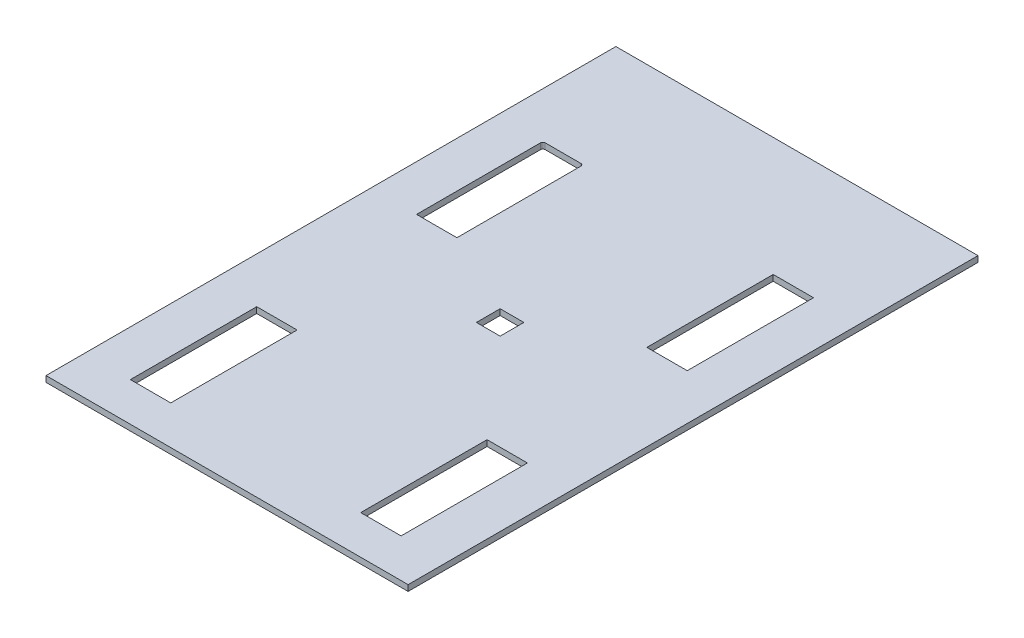
SolidWorks part; units mm, degrees
ref_plane "Front Plane" through (0, 0, 0) normal (0, 0, 1) x (1, 0, 0)
ref_plane "Top Plane" through (0, 0, 0) normal (0, 1, 0) x (1, 0, 0)
ref_plane "Right Plane" through (0, 0, 0) normal (1, 0, 0) x (0, 0, -1)
sketch "Sketch1" plane through (0, 0, 0) normal (0, 1, 0) x (1, 0, 0)
  line L1 (-193.675, -304.8) -> (193.675, -304.8)
  line L2 (-193.675, -304.8) -> (-193.675, 304.8)
  line L3 (-193.675, 304.8) -> (193.675, 304.8)
  line L4 (193.675, -304.8) -> (193.675, 304.8)
  line L5 (0, 304.8) -> (0, -304.8) construction
  line L6 (-193.675, 0) -> (193.675, 0) construction
  point P0 (0, 0)
  dimension "D1" = 387.35
  dimension "D2" = 609.6
extrude "Boss-Extrude1" add sketch "Sketch1" along normal blind 6.35
sketch "Sketch2" plane through (0, 6.35, 0) normal (0, 1, 0) x (1, 0, 0)
  line L0 (0, -1000) -> (0, 49000) construction
  line L5 (193.675, 304.8) -> (-193.675, 304.8) construction
  line L6 (101.6, -263.4234) -> (144.78, -263.4234)
  line L7 (101.6, 42.672) -> (144.78, 42.672)
  line L8 (101.6, 42.672) -> (101.6, 177.8)
  line L9 (101.6, 177.8) -> (144.78, 177.8)
  line L10 (144.78, 42.672) -> (144.78, 177.8)
  line L11 (123.19, 177.8) -> (123.19, 42.672) construction
  line L12 (101.6, 110.236) -> (144.78, 110.236) construction
  line L17 (101.6, -263.4234) -> (101.6, -128.2954)
  line L18 (101.6, -128.2954) -> (144.78, -128.2954)
  line L23 (144.78, -263.4234) -> (144.78, -128.2954)
  line L24 (123.19, -128.2954) -> (123.19, -263.4234) construction
  line L25 (101.6, -195.8594) -> (144.78, -195.8594) construction
  line L26 (-123.19, -128.2954) -> (-123.19, -263.4234) construction
  line L27 (-144.78, -263.4234) -> (-144.78, -128.2954)
  line L28 (-101.6, -263.4234) -> (-101.6, -128.2954)
  line L29 (-101.6, -263.4234) -> (-144.78, -263.4234)
  line L30 (-101.6, -195.8594) -> (-144.78, -195.8594) construction
  line L31 (-101.6, -128.2954) -> (-144.78, -128.2954)
  line L32 (-101.6, 110.236) -> (-144.78, 110.236) construction
  line L33 (-123.19, 177.8) -> (-123.19, 42.672) construction
  line L34 (-144.78, 42.672) -> (-144.78, 177.8)
  line L35 (-101.6, 177.8) -> (-144.78, 177.8)
  line L36 (-101.6, 42.672) -> (-101.6, 177.8)
  line L37 (-101.6, 42.672) -> (-144.78, 42.672)
  point P1 (123.19, -195.8594)
  point P4 (123.19, 110.236)
  point P20 (-123.19, -195.8594)
  point P29 (-123.19, 110.236)
  dimension "D1" = 135.128
  dimension "D2" = 43.18
  dimension "D3" = 135.128
  dimension "D4" = 306.0954
  dimension "D5" = 127
  dimension "D6" = 123.19
extrude "Cut-Extrude1" cut sketch "Sketch2" against normal through all
sketch "Sketch4" plane through (0, 0, 0) normal (0, 1, 0) x (1, 0, 0)
  line L5 (144.78, 177.8) -> (101.6, 177.8) construction
  line L6 (-12.7, -25.4) -> (12.7, -25.4)
  line L7 (-12.7, -25.4) -> (-12.7, 0)
  line L8 (-12.7, 0) -> (12.7, 0)
  line L9 (12.7, -25.4) -> (12.7, 0)
  line L10 (0, 0) -> (0, -25.4) construction
  line L11 (-12.7, -12.7) -> (12.7, -12.7) construction
  point P0 (0, -12.7)
  dimension "D1" = 25.4
  dimension "D2" = 177.8
  dimension "D3" = 25.4
extrude "Cut-Extrude3" cut sketch "Sketch4" along normal through all
fillet "Fillet1" radius 2.54 2 edges at (-144.78, 3.175, -177.8) (-101.6, 3.175, -177.8)
